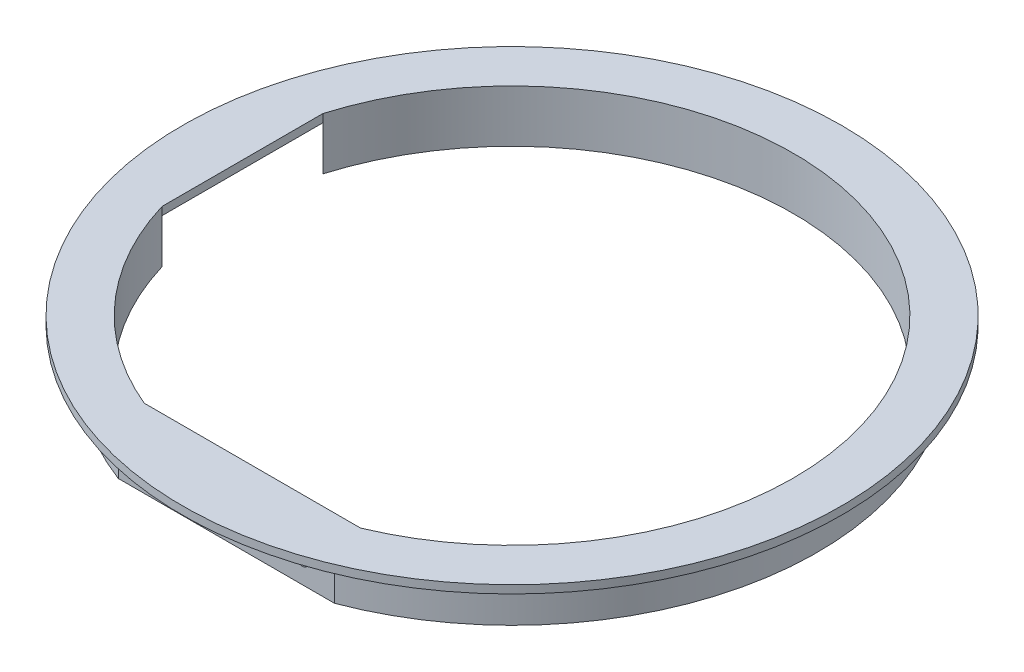
SolidWorks part; units mm, degrees
ref_plane "Front Plane" through (0, 0, 0) normal (0, 0, 1) x (1, 0, 0)
ref_plane "Top Plane" through (0, 0, 0) normal (0, 1, 0) x (1, 0, 0)
ref_plane "Right Plane" through (0, 0, 0) normal (1, 0, 0) x (0, 0, -1)
sketch "Sketch2" plane through (0, 0, 0) normal (1, 0, 0) x (0, 0, -1)
  line L0 (0, 0) -> (41, 0)
  line L1 (41, 0) -> (41, -1)
  line L2 (41, -1) -> (38, -1)
  line L3 (38, -1) -> (38, -6.5)
  line L4 (38, -6.5) -> (0, -6.5)
  line L5 (0, -6.5) -> (0, 0)
  dimension "D1" = 41
  dimension "D2" = 1
  dimension "D3" = 38
  dimension "D4" = 6.5
revolve "Revolve1" add sketch "Sketch2" angle 360 about L5
sketch "Sketch3" plane through (0, 0, 0) normal (0, 1, 0) x (1, 0, 0)
  line L0 (-20, -32.311) -> (20, -32.311) construction
  line L1 (-36.6606, -10) -> (-36.6606, 10) construction
  line L2 (-38, 0) -> (-36.6606, 0) construction
  line L3 (0, -38) -> (0, -32.311) construction
  line L4 (-13.4536, -32.311) -> (13.4536, -32.311)
  line L5 (-33.541, 10) -> (-33.541, -10)
  circle A0 centre (0, 0) radius 38 construction
  arc A1 (-33.541, -10) -> (-13.4536, -32.311) centre (0, 0) ccw
  arc A2 (13.4536, -32.311) -> (-33.541, 10) centre (0, 0) ccw
  dimension "D1" = 76
  dimension "D2" = 40
  dimension "D4" = 70
  dimension "D3" = 20
  dimension "D5" = 20
extrude "Cut-Extrude1" cut sketch "Sketch3" against normal through all
sketch "Sketch6" plane through (0, -6.5, 0) normal (0, -1, 0) x (1, 0, 0)
  line L0 (-13.4536, 35.5387) -> (13.4536, 35.5387)
  line L1 (-36.6606, -10) -> (-36.6606, 10)
  arc A0 (-13.4536, 35.5387) -> (13.4536, 35.5387) centre (0, 0) cw
  arc A1 (-36.6606, -10) -> (-36.6606, 10) centre (0, 0) cw
  circle A2 centre (0, 0) radius 38 construction
  circle A3 centre (0, 0) radius 38 construction
  dimension "D2" = 20
  dimension "D1" = 26.9072
extrude "Cut-Extrude3" cut sketch "Sketch6" against normal blind 5.5
sketch "Sketch10" plane through (-36.6606, 0, 0) normal (-1, 0, 0) x (0, 0, 1)
  line L1 (10, -6.5) -> (-10, -6.5)
  line L2 (10, -6.5) -> (10, -1)
  line L3 (10, -1) -> (-10, -1)
  line L4 (-10, -6.5) -> (-10, -1)
extrude "Cut-Extrude5" cut sketch "Sketch10" against normal blind 10
hole_wizard "Ø1.5 (1.5) Diameter Hole1" positions "Sketch9" profile "Sketch8" hole size "Ø1.5" standard "Ansi Metric"
sketch "Sketch9" plane through (0, 0, 35.5387) normal (0, 0, 1) x (1, 0, 0)
  line L0 (-13.4536, -1) -> (-13.4536, -6.5) construction
  line L1 (-41, -1) -> (41, -1) construction
  line L2 (13.4536, -1) -> (13.4536, -6.5) construction
  line L4 (1.4536, -1) -> (1.4536, -6.5) construction
  line L5 (-13.4536, -6.5) -> (13.4536, -6.5) construction
  line L7 (-1.4536, -6.5) -> (-1.4536, -1) construction
  line L8 (-13.4536, -1) -> (13.4536, -1) construction
  point P0 (9.4536, -3.75)
  point P1 (5.4536, -3.75)
  point P3 (-5.4536, -3.75)
  point P5 (-9.4536, -3.75)
  dimension "D1" = 4
  dimension "D2" = 2.75
  dimension "D3" = 4
  dimension "D4" = 4
  dimension "D5" = 4
  dimension "D6" = 12
  dimension "D7" = 12
sketch "Sketch8" plane through (9.4536, -3.75, 35.5387) normal (1, 0, 0) x (0, -1, 0)
  line L0 (0, 0) -> (0, 3.2277)
  line L1 (0, 3.2277) -> (0.75, 3.2277)
  line L2 (0.75, 3.2277) -> (0.75, 0)
  line L5 (0.75, 0) -> (0, 0)
  line L11 (0, -6.35) -> (0, 107.95) construction
  dimension "Thru Hole Dia." = 1.5
  dimension "Thru Hole Depth" = 3.2277
sketch "Sketch12" plane through (0, 0, -10) normal (0, 0, 1) x (1, 0, 0)
  line L4 (-33.541, -1) -> (-36.6606, -1)
  line L5 (-36.6606, -1) -> (-36.6606, -6.5)
  line L6 (-36.6606, -6.5) -> (-33.541, -6.5)
  line L7 (-33.541, -6.5) -> (-33.541, -1)
  line L8 (-33.541, -1) -> (-36.6606, -1)
  line L9 (-36.6606, -1) -> (-36.6606, -6.5)
  line L10 (-36.6606, -6.5) -> (-33.541, -6.5)
  line L11 (-33.541, -6.5) -> (-33.541, -1)
  dimension "D1" = 0
extrude "Cut-Extrude6" cut sketch "Sketch12" against normal through all
fillet "Fillet1" radius 1 3 edges at (-28.1232, -1, 25.5555) (0, -1, 35.5387) (28.5262, -1, -25.1048)
